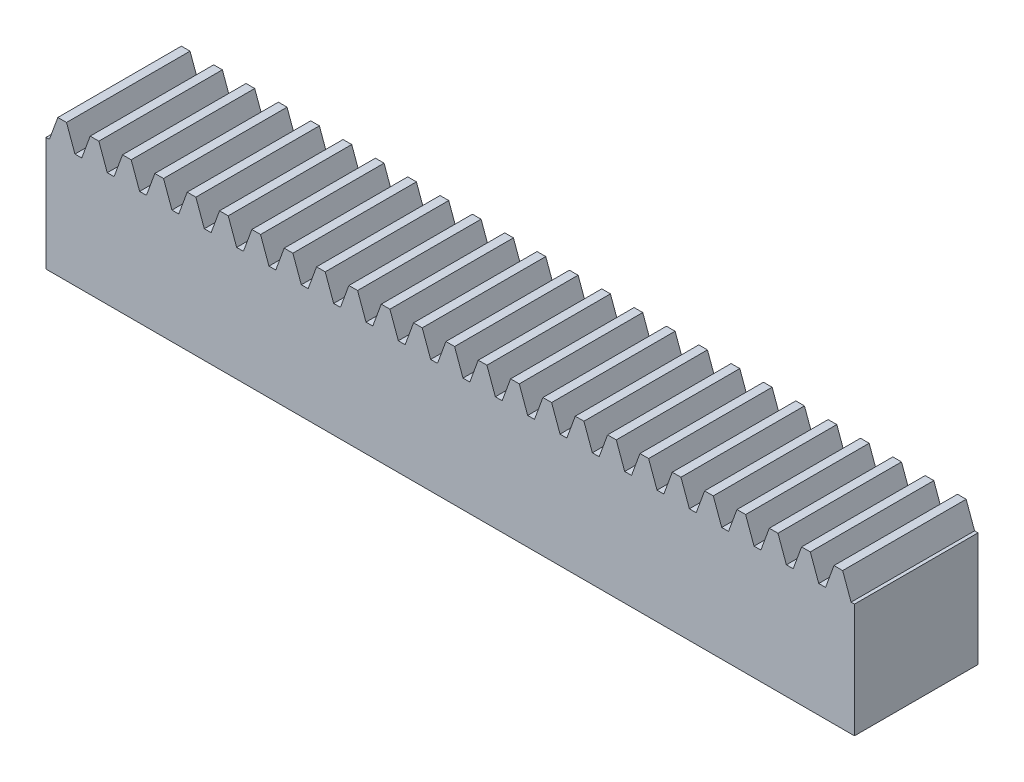
SolidWorks part; units mm, degrees
ref_plane "Plan de face" through (0, 0, 0) normal (0, 0, 1) x (1, 0, 0)
ref_plane "Plan de dessus" through (0, 0, 0) normal (0, 1, 0) x (1, 0, 0)
ref_plane "Plan de droite" through (0, 0, 0) normal (1, 0, 0) x (0, 0, -1)
ref_plane "Plan1" through (0, 0, 0) normal (0, 0, -1) x (-1, 0, 0)
sketch "Esquisse1" plane through (0, 0, 0) normal (0, 0, -1) x (-1, 0, 0)
  line L0 (-58.9049, 8.3125) -> (-58.9049, 0)
  line L1 (-58.9049, 0) -> (0, 0)
  line L2 (0, 0) -> (0, 8.3125)
  line L3 (0, 8.3125) -> (-0.2478, 8.3125)
  line L4 (-0.2478, 8.3125) -> (-0.862, 10)
  line L5 (-0.862, 10) -> (-1.4942, 10)
  line L6 (-1.4942, 10) -> (-2.1084, 8.3125)
  line L7 (-2.1084, 8.3125) -> (-2.604, 8.3125)
  line L8 (-2.604, 8.3125) -> (-3.2182, 10)
  line L9 (-3.2182, 10) -> (-3.8504, 10)
  line L10 (-3.8504, 10) -> (-4.4646, 8.3125)
  line L11 (-4.4646, 8.3125) -> (-4.9602, 8.3125)
  line L12 (-4.9602, 8.3125) -> (-5.5744, 10)
  line L13 (-5.5744, 10) -> (-6.2066, 10)
  line L14 (-6.2066, 10) -> (-6.8208, 8.3125)
  line L15 (-6.8208, 8.3125) -> (-7.3164, 8.3125)
  line L16 (-7.3164, 8.3125) -> (-7.9306, 10)
  line L17 (-7.9306, 10) -> (-8.5628, 10)
  line L18 (-8.5628, 10) -> (-9.177, 8.3125)
  line L19 (-9.177, 8.3125) -> (-9.6726, 8.3125)
  line L20 (-9.6726, 8.3125) -> (-10.2868, 10)
  line L21 (-10.2868, 10) -> (-10.9189, 10)
  line L22 (-10.9189, 10) -> (-11.5331, 8.3125)
  line L23 (-11.5331, 8.3125) -> (-12.0288, 8.3125)
  line L24 (-12.0288, 8.3125) -> (-12.643, 10)
  line L25 (-12.643, 10) -> (-13.2751, 10)
  line L26 (-13.2751, 10) -> (-13.8893, 8.3125)
  line L27 (-13.8893, 8.3125) -> (-14.385, 8.3125)
  line L28 (-14.385, 8.3125) -> (-14.9992, 10)
  line L29 (-14.9992, 10) -> (-15.6313, 10)
  line L30 (-15.6313, 10) -> (-16.2455, 8.3125)
  line L31 (-16.2455, 8.3125) -> (-16.7412, 8.3125)
  line L32 (-16.7412, 8.3125) -> (-17.3554, 10)
  line L33 (-17.3554, 10) -> (-17.9875, 10)
  line L34 (-17.9875, 10) -> (-18.6017, 8.3125)
  line L35 (-18.6017, 8.3125) -> (-19.0974, 8.3125)
  line L36 (-19.0974, 8.3125) -> (-19.7116, 10)
  line L37 (-19.7116, 10) -> (-20.3437, 10)
  line L38 (-20.3437, 10) -> (-20.9579, 8.3125)
  line L39 (-20.9579, 8.3125) -> (-21.4536, 8.3125)
  line L40 (-21.4536, 8.3125) -> (-22.0678, 10)
  line L41 (-22.0678, 10) -> (-22.6999, 10)
  line L42 (-22.6999, 10) -> (-23.3141, 8.3125)
  line L43 (-23.3141, 8.3125) -> (-23.8098, 8.3125)
  line L44 (-23.8098, 8.3125) -> (-24.424, 10)
  line L45 (-24.424, 10) -> (-25.0561, 10)
  line L46 (-25.0561, 10) -> (-25.6703, 8.3125)
  line L47 (-25.6703, 8.3125) -> (-26.166, 8.3125)
  line L48 (-26.166, 8.3125) -> (-26.7802, 10)
  line L49 (-26.7802, 10) -> (-27.4123, 10)
  line L50 (-27.4123, 10) -> (-28.0265, 8.3125)
  line L51 (-28.0265, 8.3125) -> (-28.5222, 8.3125)
  line L52 (-28.5222, 8.3125) -> (-29.1364, 10)
  line L53 (-29.1364, 10) -> (-29.7685, 10)
  line L54 (-29.7685, 10) -> (-30.3827, 8.3125)
  line L55 (-30.3827, 8.3125) -> (-30.8784, 8.3125)
  line L56 (-30.8784, 8.3125) -> (-31.4926, 10)
  line L57 (-31.4926, 10) -> (-32.1247, 10)
  line L58 (-32.1247, 10) -> (-32.7389, 8.3125)
  line L59 (-32.7389, 8.3125) -> (-33.2345, 8.3125)
  line L60 (-33.2345, 8.3125) -> (-33.8487, 10)
  line L61 (-33.8487, 10) -> (-34.4809, 10)
  line L62 (-34.4809, 10) -> (-35.0951, 8.3125)
  line L63 (-35.0951, 8.3125) -> (-35.5907, 8.3125)
  line L64 (-35.5907, 8.3125) -> (-36.2049, 10)
  line L65 (-36.2049, 10) -> (-36.8371, 10)
  line L66 (-36.8371, 10) -> (-37.4513, 8.3125)
  line L67 (-37.4513, 8.3125) -> (-37.9469, 8.3125)
  line L68 (-37.9469, 8.3125) -> (-38.5611, 10)
  line L69 (-38.5611, 10) -> (-39.1933, 10)
  line L70 (-39.1933, 10) -> (-39.8075, 8.3125)
  line L71 (-39.8075, 8.3125) -> (-40.3031, 8.3125)
  line L72 (-40.3031, 8.3125) -> (-40.9173, 10)
  line L73 (-40.9173, 10) -> (-41.5495, 10)
  line L74 (-41.5495, 10) -> (-42.1637, 8.3125)
  line L75 (-42.1637, 8.3125) -> (-42.6593, 8.3125)
  line L76 (-42.6593, 8.3125) -> (-43.2735, 10)
  line L77 (-43.2735, 10) -> (-43.9057, 10)
  line L78 (-43.9057, 10) -> (-44.5199, 8.3125)
  line L79 (-44.5199, 8.3125) -> (-45.0155, 8.3125)
  line L80 (-45.0155, 8.3125) -> (-45.6297, 10)
  line L81 (-45.6297, 10) -> (-46.2619, 10)
  line L82 (-46.2619, 10) -> (-46.8761, 8.3125)
  line L83 (-46.8761, 8.3125) -> (-47.3717, 8.3125)
  line L84 (-47.3717, 8.3125) -> (-47.9859, 10)
  line L85 (-47.9859, 10) -> (-48.6181, 10)
  line L86 (-48.6181, 10) -> (-49.2323, 8.3125)
  line L87 (-49.2323, 8.3125) -> (-49.7279, 8.3125)
  line L88 (-49.7279, 8.3125) -> (-50.3421, 10)
  line L89 (-50.3421, 10) -> (-50.9743, 10)
  line L90 (-50.9743, 10) -> (-51.5885, 8.3125)
  line L91 (-51.5885, 8.3125) -> (-52.0841, 8.3125)
  line L92 (-52.0841, 8.3125) -> (-52.6983, 10)
  line L93 (-52.6983, 10) -> (-53.3304, 10)
  line L94 (-53.3304, 10) -> (-53.9446, 8.3125)
  line L95 (-53.9446, 8.3125) -> (-54.4403, 8.3125)
  line L96 (-54.4403, 8.3125) -> (-55.0545, 10)
  line L97 (-55.0545, 10) -> (-55.6866, 10)
  line L98 (-55.6866, 10) -> (-56.3008, 8.3125)
  line L99 (-56.3008, 8.3125) -> (-56.7965, 8.3125)
  line L100 (-56.7965, 8.3125) -> (-57.4107, 10)
  line L101 (-57.4107, 10) -> (-58.0428, 10)
  line L102 (-58.0428, 10) -> (-58.657, 8.3125)
  line L103 (-58.657, 8.3125) -> (-58.9049, 8.3125)
  dimension "D1" = 0.2478
  dimension "D2" = 0.6321
  dimension "D3" = 1.6875
  dimension "D4" = 0.4957
  dimension "D5" = 0.6142
extrude "Boss.-Extru.1" add sketch "Esquisse1" against normal blind 9
